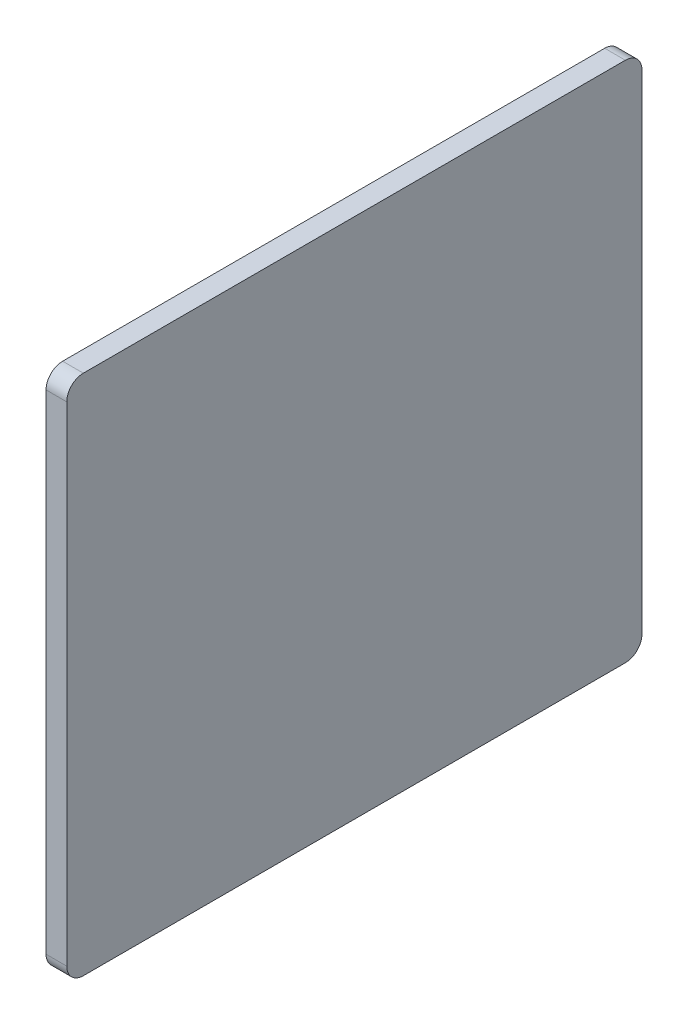
SolidWorks part; units mm, degrees
material "Acrylic (Medium-high impact)"
ref_plane "Front Plane" through (0, 0, 0) normal (0, 0, 1) x (1, 0, 0)
ref_plane "Top Plane" through (0, 0, 0) normal (0, 1, 0) x (1, 0, 0)
ref_plane "Right Plane" through (0, 0, 0) normal (1, 0, 0) x (0, 0, -1)
sketch "Sketch1" plane through (0, 0, 0) normal (1, 0, 0) x (0, 0, -1)
  line L1 (44.0875, -40) -> (-44.0875, -40)
  line L2 (44.0875, -40) -> (44.0875, 40)
  line L3 (44.0875, 40) -> (-44.0875, 40)
  line L4 (-44.0875, -40) -> (-44.0875, 40)
  line L5 (44.0875, -40) -> (-44.0875, 40) construction
  line L6 (44.0875, 40) -> (-44.0875, -40) construction
  point P0 (0, 0)
  dimension "D1" = 88.175
  dimension "D2" = 80
extrude "Boss-Extrude1" add sketch "Sketch1" along normal blind 3.175
fillet "Fillet1" radius 2.54 4 edges at (1.5875, -40, 44.0875) (1.5875, -40, -44.0875) (1.5875, 40, -44.0875) (1.5875, 40, 44.0875)
